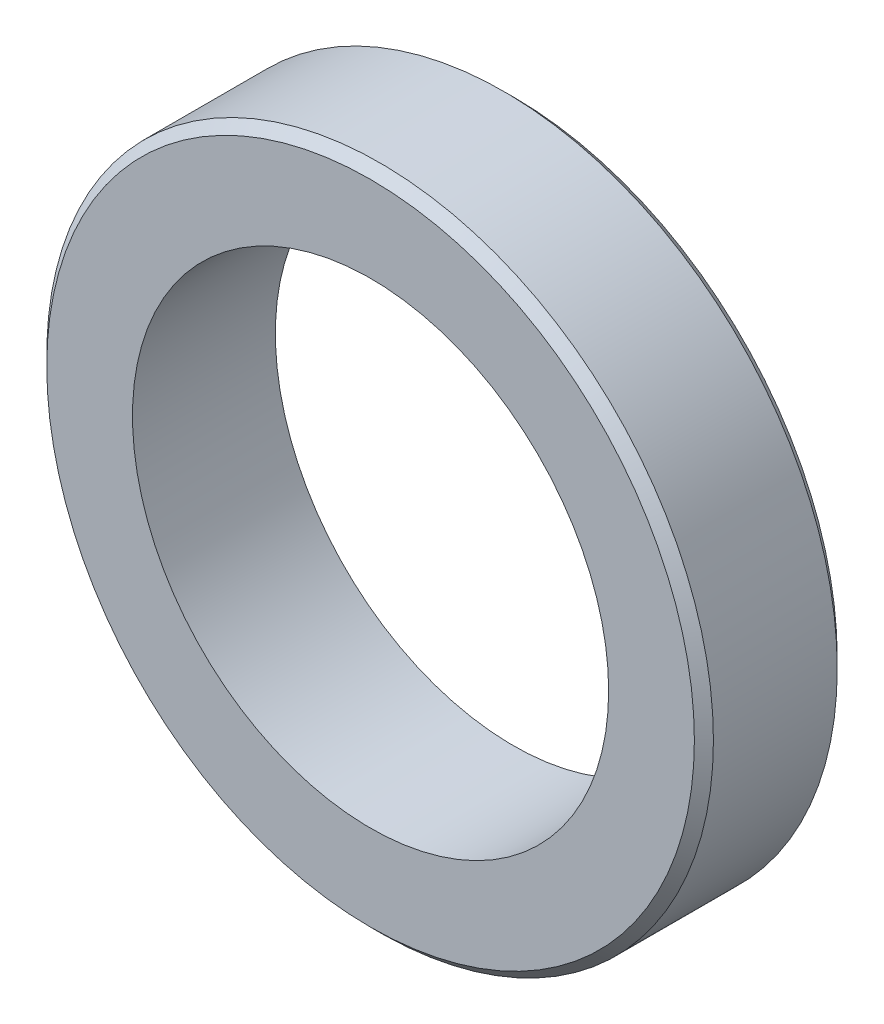
SolidWorks part; units mm, degrees
material "1060-H12 棒材(SS)"
ref_plane "前视基准面" through (0, 0, 0) normal (0, 0, 1) x (1, 0, 0)
ref_plane "上视基准面" through (0, 0, 0) normal (0, 1, 0) x (1, 0, 0)
ref_plane "右视基准面" through (0, 0, 0) normal (1, 0, 0) x (0, 0, -1)
sketch "草图1" plane through (0, 0, 0) normal (0, 0, 1) x (1, 0, 0)
  circle A0 centre (0, 0) radius 25
  circle A1 centre (0, 0) radius 35
  dimension "D1" = 50
  dimension "D2" = 70
extrude "凸台-拉伸1" add sketch "草图1" along normal blind 15
chamfer "倒角1" distance 1 angle 45 2 edges at (35, 0, 15) (35, 0, 0)
